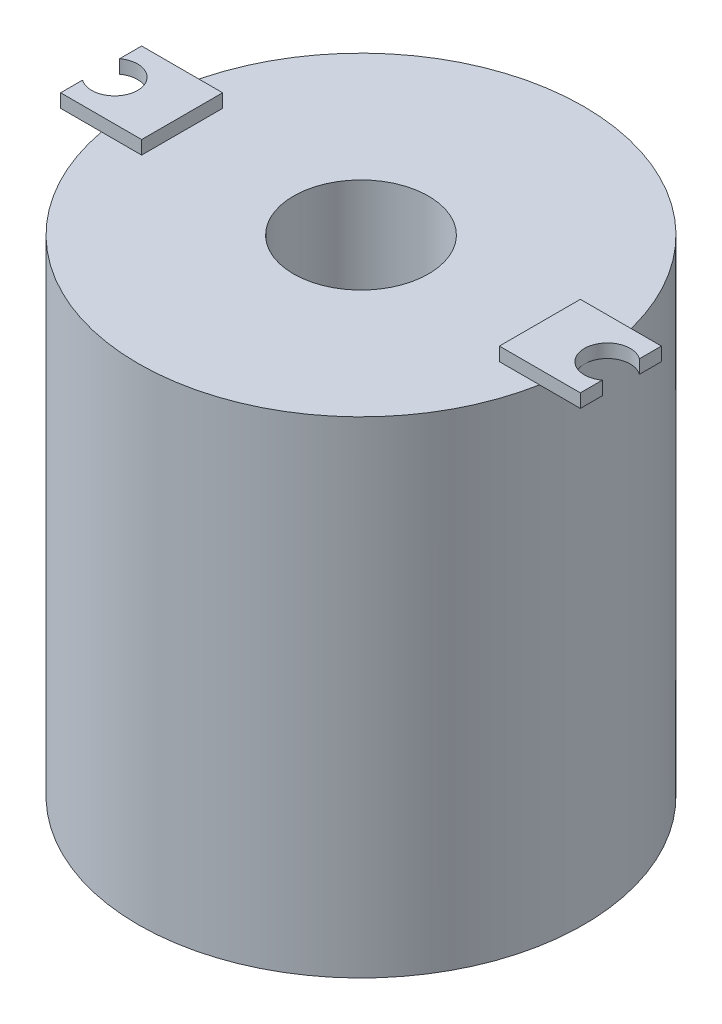
SolidWorks part; units mm, degrees
ref_plane "Front Plane" through (0, 0, 0) normal (0, 0, 1) x (1, 0, 0)
ref_plane "Top Plane" through (0, 0, 0) normal (0, 1, 0) x (1, 0, 0)
ref_plane "Right Plane" through (0, 0, 0) normal (1, 0, 0) x (0, 0, -1)
sketch "Sketch1" plane through (0, 0, 0) normal (0, 1, 0) x (1, 0, 0)
  circle A0 centre (0, 0) radius 16.5
  circle A1 centre (0, 0) radius 5
  dimension "D1" = 33
  dimension "D2" = 10
extrude "Boss-Extrude1" add sketch "Sketch1" along normal blind 36
sketch "Sketch2" plane through (0, 36, 0) normal (0, 1, 0) x (1, 0, 0)
  line L0 (18.25, 3) -> (18.25, -3) construction
  line L1 (13.25, 3) -> (19.25, 3)
  line L2 (13.25, 3) -> (13.25, -3)
  line L3 (13.25, -3) -> (19.25, -3)
  line L4 (19.25, 3) -> (19.25, -3)
  point P6 (19.25, 0)
  dimension "D1" = 6
  dimension "D2" = 6
  dimension "D3" = 1
  dimension "D4" = 18.25
extrude "Boss-Extrude2" add sketch "Sketch2" along normal blind 1
hole_wizard "M3 Clearance Hole1" positions "Sketch3" profile "Sketch4" hole size "M3" standard "ANSI Metric" end condition up to next
sketch "Sketch3" plane through (0, 37, 0) normal (0, 1, 0) x (1, 0, 0)
  point P0 (18.25, 0)
  point P8 (0, 0)
  dimension "D1" = 18.25
sketch "Sketch4" plane through (18.25, 37, 0) normal (1, 0, 0) x (0, 0, 1)
  line L0 (0, 0) -> (0, 1)
  line L1 (0, 1) -> (1.7, 1)
  line L2 (1.7, 1) -> (1.7, 0)
  line L5 (1.7, 0) -> (0, 0)
  line L11 (0, -6.35) -> (0, 107.95) construction
  dimension "Thru Hole Dia." = 3.4
  dimension "Thru Hole Depth" = 1
mirror "Mirror1" about plane through (0, 0, 0) normal (1, 0, 0) of "M3 Clearance Hole1", "Boss-Extrude2"
